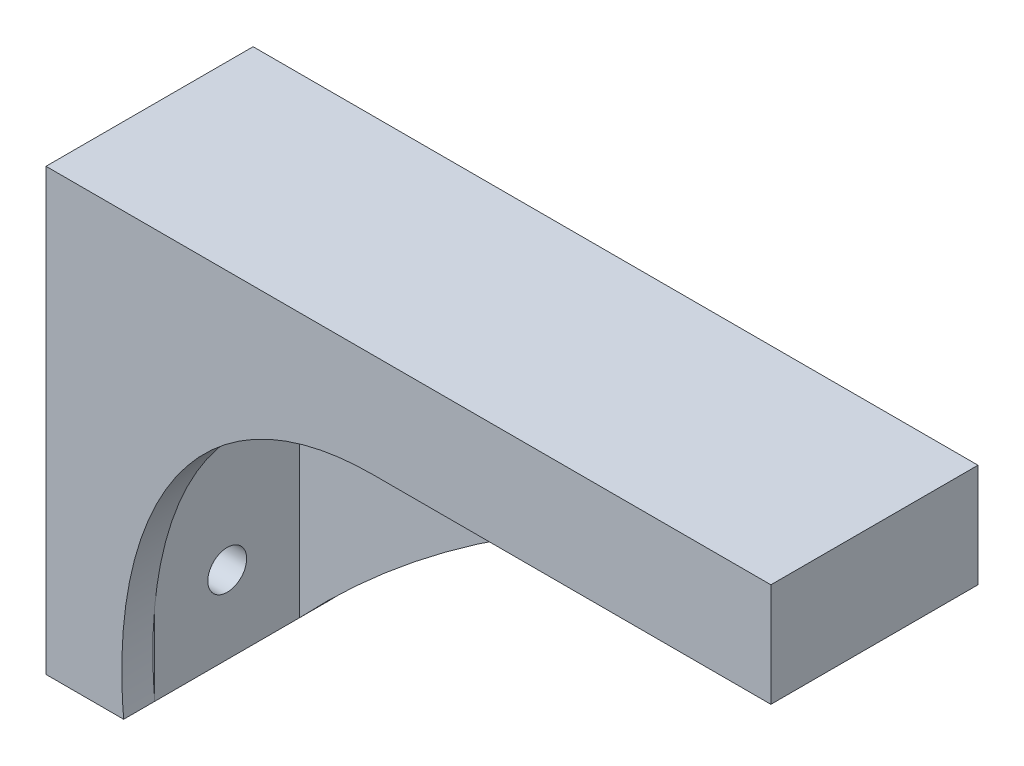
SolidWorks part; units mm, degrees
material "Nylon 101"
ref_plane "Front Plane" through (0, 0, 0) normal (0, 0, 1) x (1, 0, 0)
ref_plane "Top Plane" through (0, 0, 0) normal (0, 1, 0) x (1, 0, 0)
ref_plane "Right Plane" through (0, 0, 0) normal (1, 0, 0) x (0, 0, -1)
sketch "Sketch1" plane through (0, 0, 0) normal (0, 0, 1) x (1, 0, 0)
  line L0 (0, 0) -> (0, -107.95)
  line L2 (177.8, 0) -> (0, 0)
  line L3 (0, -107.95) -> (19.05, -107.95)
  line L5 (177.8, -25.4) -> (177.8, 0)
  line L6 (19.05, -107.95) -> (19.05, -25.4)
  line L7 (19.05, -25.4) -> (177.8, -25.4)
  dimension "D1" = 107.95
  dimension "D2" = 19.05
  dimension "D3" = 25.4
  dimension "D4" = 177.8
extrude "Boss-Extrude1" add sketch "Sketch1" along normal blind 50.8
sketch "Sketch2" plane through (0, 0, 0) normal (-1, 0, 0) x (0, 0, 1)
  line L0 (25.4, 0) -> (25.4, -107.95) construction
  line L1 (50.8, 0) -> (0, 0) construction
  line L2 (50.8, -107.95) -> (0, -107.95) construction
  point P6 (25.4, -31.75)
  point P7 (25.4, -88.9)
  dimension "D1" = 57.15
  dimension "0.5" = 19.05
hole_wizard "#8 Clearance Hole1" positions "Sketch3" profile "Sketch4" hole size "#8" standard "ANSI Inch" end condition through all
sketch "Sketch3" plane through (0, 0, 0) normal (-1, 0, 0) x (0, 0, 1)
  point P0 (25.4, -31.75)
  point P3 (25.4, -88.9)
sketch "Sketch4" plane through (0, -31.75, 25.4) normal (0, 1, 0) x (0, 0, 1)
  line L0 (0, 0) -> (0, 177.8)
  line L1 (0, 177.8) -> (2.2479, 177.8)
  line L2 (2.2479, 177.8) -> (2.2479, 0)
  line L5 (2.2479, 0) -> (0, 0)
  line L11 (0, -6.35) -> (0, 107.95) construction
  dimension "Thru Hole Dia." = 4.4958
  dimension "Thru Hole Depth" = 177.8
hole_wizard "CBORE for #8 Binding Head Machine Screw1" positions "Sketch5" profile "Sketch6" counterbore size "#8" standard "ANSI Inch" end condition through all
sketch "Sketch5" plane through (19.05, 0, 0) normal (1, 0, 0) x (0, 0, -1)
  point P0 (-25.4, -31.75)
  point P3 (-25.4, -88.9)
sketch "Sketch6" plane through (19.05, -31.75, 25.4) normal (0, 1, 0) x (0, 0, -1)
  line L0 (0, 0) -> (0, 19.05)
  line L1 (0, 19.05) -> (2.2479, 19.05)
  line L3 (2.2479, 19.05) -> (2.2479, 12.7)
  line L4 (2.2479, 12.7) -> (4.7625, 12.7)
  line L5 (4.7625, 12.7) -> (4.7625, 0)
  line L7 (4.7625, 0) -> (0, 0)
  line L11 (0, -6.35) -> (0, 107.95) construction
  dimension "Thru Hole Dia." = 4.4958
  dimension "Thru Hole Depth" = 19.05
  dimension "C'Bore Dia." = 9.525
  dimension "C'Bore Depth" = 12.7
sketch "Sketch7" plane through (0, 0, 50.8) normal (0, 0, 1) x (1, 0, 0)
  line L4 (19.05, -107.95) -> (19.05, -25.4)
  line L5 (19.05, -25.4) -> (177.8, -25.4)
  line L6 (19.05, -25.4) -> (177.8, -25.4) construction
  arc A1 (19.05, -107.95) -> (177.8, -25.4) centre (216.7199, -294.1652) cw
extrude "Boss-Extrude2" add sketch "Sketch7" against normal blind 7.62
ref_plane "Plane1" through (0, 0, 25.4) normal (0, 0, -1) x (-1, 0, 0)
mirror "Mirror1" about plane through (0, 0, 25.4) normal (0, 0, -1) of "Boss-Extrude2"
sketch "Sketch8" plane through (0, 0, 50.8) normal (0, 0, 1) x (1, 0, 0)
  line L0 (177.8, -25.4) -> (80.2736, -25.4)
  line L1 (19.05, -107.95) -> (177.8, -25.4)
  spline S0 degree 3 poles (80.2736, -25.4) (36.8715, -25.4) (15.0651, -63.5273) (19.05, -107.95) knots 0 0 0 0 1 1 1 1
extrude "Cut-Extrude1" cut sketch "Sketch8" against normal blind 7.62
